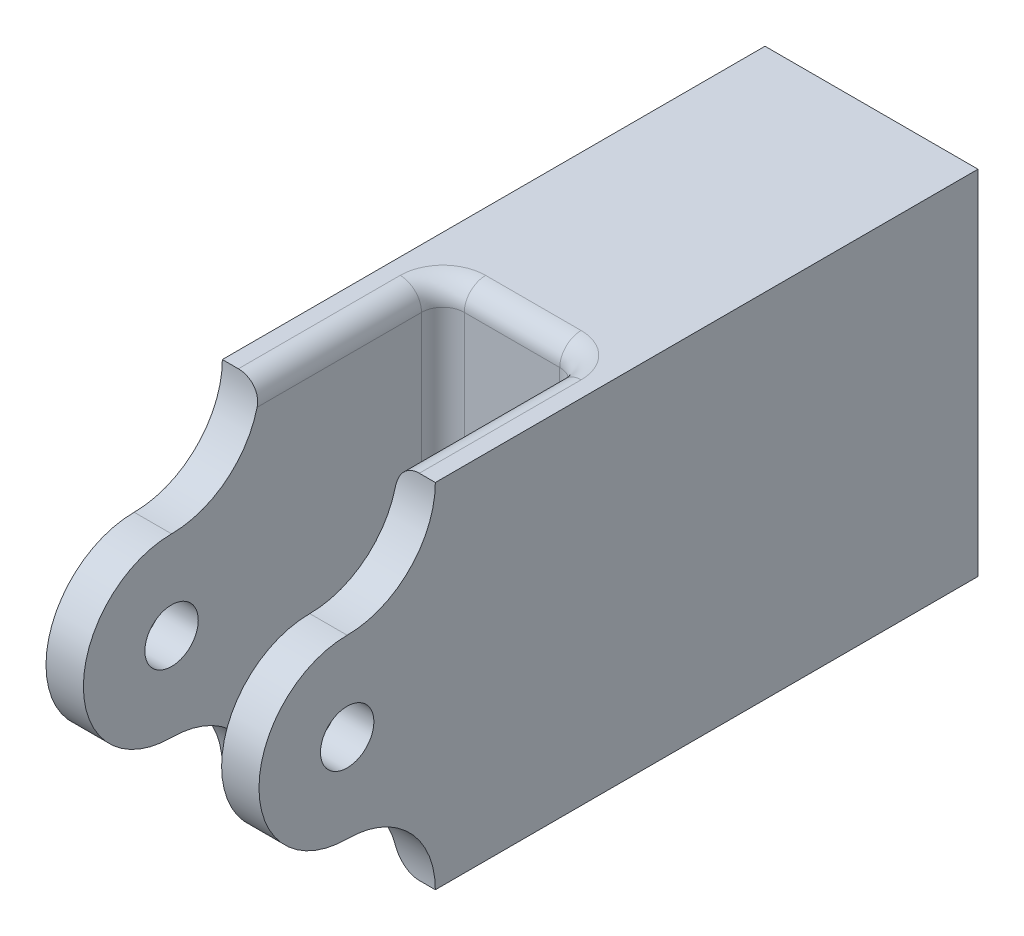
SolidWorks part; units mm, degrees
ref_plane "Front Plane" through (0, 0, 0) normal (1, 0, 0) x (0, 1, 0)
ref_plane "Top Plane" through (0, 0, 0) normal (0, 0, 1) x (0, 1, 0)
ref_plane "Right Plane" through (0, 0, 0) normal (0, 1, 0) x (-1, 0, 0)
sketch "Sketch2" plane through (0, 0, 0) normal (1, 0, 0) x (0, 1, 0)
  line L0 (-33.02, 0) -> (33.02, 0)
  line L1 (-33.02, 0) -> (-33.02, 101.6)
  line L2 (33.02, 0) -> (33.02, 101.6)
  arc A0 (-16.51, 118.11) -> (16.51, 118.11) centre (0, 118.11) cw
  arc A1 (16.51, 118.11) -> (33.02, 101.6) centre (33.02, 118.11) ccw
  arc A2 (-16.51, 118.11) -> (-33.02, 101.6) centre (-33.02, 118.11) cw
  circle A3 centre (0, 118.11) radius 5
  dimension "D1" = 10
  dimension "D2" = 66.04
  dimension "D3" = 101.6
extrude "Boss-Extrude1" add sketch "Sketch2" along normal mid plane 39.878
sketch "Sketch3" plane through (0, 0, 0) normal (0, 1, 0) x (-1, 0, 0)
  line L0 (19.939, 0) -> (19.939, 101.6) construction
  line L1 (12.939, 134.62) -> (-12.939, 134.62)
  line L2 (12.939, 134.62) -> (12.939, 67.31)
  line L3 (12.939, 67.31) -> (-12.939, 67.31)
  line L4 (-12.939, 134.62) -> (-12.939, 67.31)
  line L5 (12.939, 134.62) -> (-12.939, 67.31) construction
  line L6 (12.939, 67.31) -> (-12.939, 134.62) construction
  line L7 (19.939, 134.62) -> (-19.939, 134.62) construction
  line L8 (19.939, 134.62) -> (19.939, 0)
  point P0 (0, 100.965)
  point P14 (19.939, 67.31)
  dimension "D1" = 7
extrude "Cut-Extrude1" cut sketch "Sketch3" against normal through all both and the other way through all contours L1 L4 L3 L2
fillet "Fillet1" radius 4 8 edges at (0, 33.02, 67.31) (0, -33.02, 67.31) (12.939, 0, 67.31) (-12.939, 0, 67.31) (12.939, 33.02, 84.455) (-12.939, 33.02, 84.455) (12.939, -33.02, 84.455) (-12.939, -33.02, 84.455)
